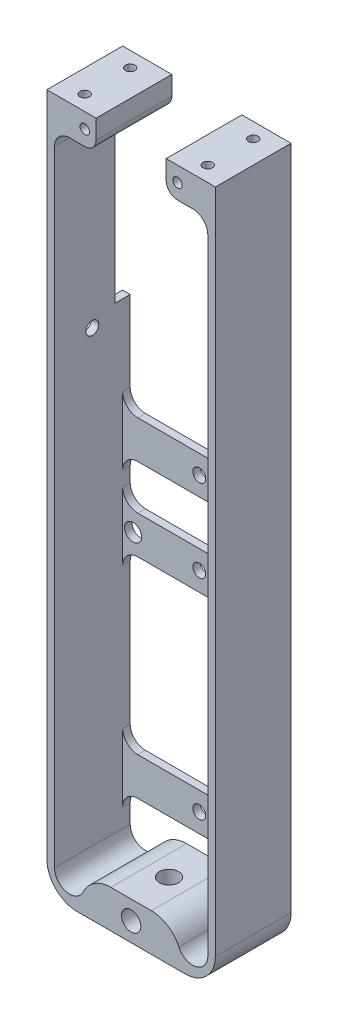
SolidWorks part; units mm, degrees
material "Сплав 2024"
ref_plane "Спереди" through (0, 0, 0) normal (0, 0, 1) x (1, 0, 0)
ref_plane "Сверху" through (0, 0, 0) normal (0, 1, 0) x (1, 0, 0)
ref_plane "Справа" through (0, 0, 0) normal (1, 0, 0) x (0, 0, -1)
sketch "Эскиз1" plane through (0, 0, 0) normal (0, 0, 1) x (1, 0, 0)
  line L0 (-2, -7) -> (42.5, -7)
  line L1 (8, 3) -> (32.5, 3)
  line L2 (0, 0) -> (0, 173)
  line L3 (0, 173) -> (40.5, 173)
  line L4 (40.5, 0) -> (40.5, 173)
  line L5 (42.5, -7) -> (42.5, 175)
  line L6 (-2, 175) -> (42.5, 175)
  line L7 (-2, -7) -> (-2, 175)
  line L8 (8, 0) -> (8, 3)
  line L9 (32.5, 0) -> (32.5, 3)
  arc A0 (0, 0) -> (8, 0) centre (4, 0) ccw
  arc A1 (32.5, 0) -> (40.5, 0) centre (36.5, 0) ccw
  dimension "D6" = 8
  dimension "D7" = 8
  dimension "D1" = 40.5
  dimension "D2" = 170
  dimension "D3" = 10
  dimension "D4" = 2
  dimension "D5" = 2
  dimension "D8" = 2
  dimension "D9" = 7
extrude "Бобышка-Вытянуть1" add sketch "Эскиз1" along normal blind 20
fillet "Скругление1" radius 8 4 edges at (42.5, -7, 10) (-2, -7, 10) (32.5, 3, 10) (8, 3, 10)
sketch "Эскиз2" plane through (0, -7, 0) normal (0, -1, 0) x (1, 0, 0)
  line L0 (20.25, 20) -> (20.25, 0) construction
  line L1 (6, 20) -> (34.5, 20) construction
  line L2 (6, 0) -> (34.5, 0) construction
  line L3 (34.5, 10) -> (6, 10) construction
  line L4 (34.5, 0) -> (34.5, 20) construction
  line L5 (6, 20) -> (6, 0) construction
hole_wizard "Отверстие обработанное метчиком 1/4-201" positions "Эскиз4" profile "Эскиз3" tap size "1/4-20" standard "Ansi Inch"
sketch "Эскиз4" plane through (0, -7, 0) normal (0, -1, 0) x (-1, 0, 0)
  line L0 (-20.25, -20) -> (-20.25, 0) construction
  point P0 (-20.25, -10)
sketch "Эскиз3" plane through (20.25, -7, 10) normal (1, 0, 0) x (0, 0, -1)
  line L0 (0, 0) -> (0, 10)
  line L1 (0, 10) -> (2.5527, 10)
  line L2 (2.5527, 10) -> (2.5527, 0)
  line L5 (2.5527, 0) -> (0, 0)
  line L11 (0, -6.35) -> (0, 107.95) construction
  dimension "Диаметр проходного сверла" = 5.1054
  dimension "Глубина проходного сверла" = 10
cosmetic thread "Отверстие резьбы1" parameters "D2"=6.35
ref_plane "Плоскость1" through (0, 158, 0) normal (0, 1, 0) x (1, 0, 0)
sketch "Эскиз5" plane through (0, 0, 20) normal (0, 0, 1) x (1, 0, 0)
  line L0 (-7.1, 158) -> (-7.1, 132.6982) construction
  line L2 (-7.1, 158) -> (-7.1, 139)
  line L3 (17.5494, 158) -> (-17.5494, 158) construction
  line L4 (0, 173) -> (0, 0) construction
  line L5 (-9.1, 158) -> (-9.1, 139)
  line L6 (-2, 113.3175) -> (-2, 117.4689)
  line L7 (-2, 175) -> (-2, 1) construction
  line L8 (-9.1, 158) -> (-7.1, 158)
  arc A0 (-9.1, 139) -> (-2, 113.3175) centre (40.9, 139) ccw
  arc A1 (-7.1, 139) -> (-2, 117.4689) centre (40.9, 139) ccw
  dimension "D4" = 100
  dimension "D1" = 7.1
  dimension "D2" = 19
  dimension "D3" = 2
extrude "Бобышка-Вытянуть2" add sketch "Эскиз5" against normal up to surface (20 mm away) up to face at (20.25, 55.781, 0)
fillet "Скругление2" radius 100 1 edges at (-2, 113.3175, 10)
sketch "Эскиз6" plane through (0, 0, 20) normal (0, 0, 1) x (1, 0, 0)
  line L2 (0, 173) -> (0, 117.4689)
  line L3 (0, 117.4689) -> (-2, 117.4689)
  line L4 (-2, 170) -> (-2, 117.4689)
  line L5 (42.5, 175) -> (-2, 175)
  line L6 (42.5, 175) -> (42.5, 173)
  line L7 (42.5, 173) -> (0, 173)
  line L8 (-2, 175) -> (-2, 170)
extrude "Вырез-Вытянуть1" cut sketch "Эскиз6" against normal up to next
sketch "Эскиз7" plane through (-9.1, 0, 0) normal (-1, 0, 0) x (0, 0, 1)
  line L0 (10, 158) -> (10, 133.3641) construction
  line L1 (0, 158) -> (20, 158) construction
  circle A0 centre (10, 145.4263) radius 5.25
  dimension "D1" = 10.5
extrude "Вырез-Вытянуть2" cut sketch "Эскиз7" against normal up to next
sketch "Эскиз9" plane through (0, 0, 20) normal (0, 0, 1) x (1, 0, 0)
  line L0 (-6.8233, 133.8533) -> (0, 133.8533)
  line L1 (0, 133.8533) -> (0, 117.4689)
  line L2 (-2, 117.4689) -> (0, 117.4689) construction
  line L3 (-2, 117.4689) -> (0, 117.4689)
  arc A0 (-7.1, 139) -> (-2, 117.4689) centre (40.9, 139) ccw construction
  arc A1 (-6.8233, 133.8533) -> (-2, 117.4689) centre (40.9, 139) ccw
extrude "Бобышка-Вытянуть3" add sketch "Эскиз9" against normal up to surface (20 mm away) up to face at (12.0849, 68.7632, 0)
fillet "Скругление7" radius 4 1 edges at (-6.8233, 133.8533, 10)
sketch "Эскиз10" plane through (0, 0, 20) normal (0, 0, 1) x (1, 0, 0)
  line L0 (17.5494, 158) -> (-17.5494, 158) construction
  line L1 (-9.1, 158) -> (-7.1, 158)
  line L2 (-9.1, 158) -> (-9.1, 172.1367)
  line L3 (-9.1, 172.1367) -> (-7.1, 172.1367)
  line L4 (-7.1, 158) -> (-7.1, 172.1367)
  line L5 (-9.1, 158) -> (-9.1, 139) construction
extrude "Бобышка-Вытянуть4" add sketch "Эскиз10" against normal up to surface (20 mm away) up to face at (11.1424, 73.5841, 0)
sketch "Эскиз11" plane through (-9.1, 0, 0) normal (-1, 0, 0) x (0, 0, 1)
  line L0 (10, 145.4263) -> (10, 162.0459) construction
  circle A0 centre (10, 162.4263) radius 4.1
  dimension "D1" = 8.2
  dimension "D2" = 17
extrude "Вырез-Вытянуть3" cut sketch "Эскиз11" against normal up to next
sketch "Эскиз12" plane through (0, 0, 20) normal (0, 0, 1) x (1, 0, 0)
  line L1 (42.5, 169.6552) -> (-9.1, 169.6552)
  line L2 (42.5, 169.6552) -> (42.5, 175.3281)
  line L3 (42.5, 175.3281) -> (-9.1, 175.3281)
  line L4 (-9.1, 169.6552) -> (-9.1, 175.3281)
extrude "Вырез-Вытянуть4" cut sketch "Эскиз12" against normal up to next
sketch "Эскиз13" plane through (0, 0, 20) normal (0, 0, 1) x (1, 0, 0)
  line L0 (36.5, 175.6552) -> (-3.1, 175.6552)
  line L1 (40.5, 0) -> (40.5, 169.6552) construction
  line L2 (-7.1, 139) -> (-7.1, 169.6552) construction
  line L3 (40.5, 0) -> (40.5, 169.6552) construction
  line L4 (-7.1, 169.6552) -> (-9.1, 169.6552)
  line L5 (42.5, 169.6552) -> (40.5, 169.6552)
  line L6 (-3.1, 173.6552) -> (36.5, 173.6552)
  line L7 (42.5, 1) -> (42.5, 169.6552) construction
  arc A0 (40.5, 169.6552) -> (36.5, 173.6552) centre (36.5, 169.6552) ccw
  arc A1 (-9.1, 169.6552) -> (-3.1, 175.6552) centre (-3.1, 169.6552) cw
  arc A2 (42.5, 169.6552) -> (36.5, 175.6552) centre (36.5, 169.6552) ccw
  arc A4 (-7.1, 169.6552) -> (-3.1, 173.6552) centre (-3.1, 169.6552) cw
  dimension "D1" = 4
  dimension "D2" = 4
extrude "Бобышка-Вытянуть5" add sketch "Эскиз13" against normal up to surface (20 mm away) up to face at (11.1424, 74.3756, 0)
ref_plane "Плоскость2" through (20.25, 0, 0) normal (1, 0, 0) x (0, 0, -1)
ref_plane "Плоскость3" through (0, 0, 10) normal (0, 0, 1) x (1, 0, 0)
sketch "Эскиз14" plane through (0, 0, 20) normal (0, 0, 1) x (1, 0, 0)
  line L1 (-2, 93.3975) -> (-11.1755, 93.3975)
  line L2 (-2, 93.3975) -> (-2, 176.4851)
  line L3 (-2, 176.4851) -> (-11.1755, 176.4851)
  line L4 (-11.1755, 93.3975) -> (-11.1755, 176.4851)
extrude "Вырез-Вытянуть5" cut sketch "Эскиз14" against normal through all
sketch "Эскиз15" plane through (0, 0, 20) normal (0, 0, 1) x (1, 0, 0)
  line L0 (36.5, 175.6552) -> (-2, 175.6552) construction
  line L1 (-2, 173.6552) -> (3, 173.6552)
  line L2 (-2, 173.6552) -> (-2, 168.6552)
  line L3 (-2, 168.6552) -> (3, 168.6552)
  line L4 (3, 173.6552) -> (3, 168.6552)
  dimension "D1" = 7
  dimension "D2" = 5
extrude "Бобышка-Вытянуть6" add sketch "Эскиз15" against normal up to surface (20 mm away) up to face at (19.6984, 71.7247, 0)
fillet "Скругление10" radius 4 1 edges at (3, 173.6552, 10)
sketch "Эскиз17" plane through (0, 0, 20) normal (0, 0, 1) x (1, 0, 0)
  line L0 (0, 133.8533) -> (0, 0) construction
  line L1 (-2, 133.8533) -> (0, 133.8533)
  line L2 (-2, 133.8533) -> (-2, 121.9315)
  line L3 (-2, 121.9315) -> (0, 121.9315)
  line L4 (0, 133.8533) -> (0, 121.9315)
hole_wizard "Отверстие с зазором M31" positions "Эскиз20" profile "Эскиз19" hole size "M3" standard "Ansi Metric"
sketch "Эскиз20" plane through (0, -2.5175, -0.8809) normal (-1, 0, 0) x (0, 0, 1)
  point P0 (10.8809, 121.0204)
sketch "Эскиз19" plane through (0, 118.5029, 10) normal (0, 1, 0) x (0, 0, -1)
  line L0 (0, 0) -> (0, 2)
  line L1 (0, 2) -> (1.7, 2)
  line L2 (1.7, 2) -> (1.7, 0)
  line L5 (1.7, 0) -> (0, 0)
  line L11 (0, -6.35) -> (0, 107.95) construction
  dimension "Диаметр сквозного отверстия" = 3.4
  dimension "Глубина сквозного отверстия" = 2
sketch "Эскиз21" plane through (0, 0, 20) normal (0, 0, 1) x (1, 0, 0)
  line L0 (-2, 168.6552) -> (3, 168.6552) construction
  line L1 (-2, 133.8533) -> (0, 133.8533)
  line L2 (-2, 133.8533) -> (-2, 168.6552)
  line L3 (-2, 168.6552) -> (0, 168.6552)
  line L4 (0, 133.8533) -> (0, 168.6552)
  line L5 (0, 133.8533) -> (-2, 133.8533) construction
extrude "Бобышка-Вытянуть7" add sketch "Эскиз21" against normal up to surface (20 mm away) up to face at (17.4639, 85.659, 0)
sketch "Эскиз23" plane through (0, 0, 20) normal (0, 0, 1) x (1, 0, 0)
  line L0 (42.5, 1) -> (42.5, 169.6552) construction
  line L1 (-2, 175.6552) -> (42.5, 175.6552)
  line L2 (-2, 175.6552) -> (-2, 166.9129)
  line L3 (-2, 166.9129) -> (42.5, 166.9129)
  line L4 (42.5, 175.6552) -> (42.5, 166.9129)
extrude "Вырез-Вытянуть8" cut sketch "Эскиз23" against normal through all
sketch "Эскиз24" plane through (-2, 0, 0) normal (-1, 0, 0) x (0, 0, 1)
  line L0 (10, 118.5029) -> (10, 170.933) construction
sketch "Эскиз30" plane through (0, 0, 20) normal (0, 0, 1) x (1, 0, 0)
  line L1 (40.5, 166.9129) -> (42.5, 166.9129)
  line L2 (40.5, 166.9129) -> (40.5, 177.0029)
  line L3 (40.5, 177.0029) -> (42.5, 177.0029)
  line L4 (42.5, 166.9129) -> (42.5, 177.0029)
  line L5 (0, 166.9129) -> (-2, 166.9129)
  line L6 (0, 166.9129) -> (0, 177.0029)
  line L7 (0, 177.0029) -> (-2, 177.0029)
  line L8 (-2, 166.9129) -> (-2, 177.0029)
  dimension "D1" = 10.09
extrude "Бобышка-Вытянуть9" add sketch "Эскиз30" against normal up to surface (20 mm away) up to face at (20.25, 46.4991, 0)
sketch "Эскиз27" plane through (42.5, 0, 0) normal (1, 0, 0) x (0, 0, -1)
  line L0 (-11.7, 163.0029) -> (-8.3, 163.0029) construction
  line L1 (-11.7, 166.7029) -> (-8.3, 166.7029)
  line L2 (-11.7, 159.3029) -> (-8.3, 159.3029)
  line L3 (-10, 177.0029) -> (-10, 153.6202) construction
  line L5 (0, 177.0029) -> (-20, 177.0029) construction
  arc A0 (-11.7, 166.7029) -> (-11.7, 159.3029) centre (-11.7, 163.0029) ccw
  arc A1 (-8.3, 159.3029) -> (-8.3, 166.7029) centre (-8.3, 163.0029) ccw
  point P2 (-10, 163.0029)
  dimension "D1" = 3.7
  dimension "D2" = 3.4
  dimension "D3" = 14
extrude "Вырез-Вытянуть9" cut sketch "Эскиз27" against normal up to next
ref_plane "Плоскость4" through (0, 0, 4.6) normal (0, 0, 1) x (1, 0, 0)
sketch "Эскиз32" plane through (0, 0, 20) normal (0, 0, 1) x (1, 0, 0)
  line L1 (0, 177.0029) -> (5, 177.0029)
  line L2 (0, 177.0029) -> (0, 174.0029)
  line L3 (0, 174.0029) -> (5, 174.0029)
  line L4 (5, 177.0029) -> (5, 174.0029)
  line L5 (40.5, 177.0029) -> (35.5, 177.0029)
  line L6 (40.5, 177.0029) -> (40.5, 174.0029)
  line L7 (40.5, 174.0029) -> (35.5, 174.0029)
  line L8 (35.5, 177.0029) -> (35.5, 174.0029)
  dimension "D1" = 5
  dimension "D2" = 5
  dimension "D3" = 3
extrude "Бобышка-Вытянуть10" add sketch "Эскиз32" against normal up to surface (20 mm away) up to face at (20.25, 49.382, 0)
fillet "Скругление18" radius 4 2 edges at (40.5, 174.0029, 10) (0, 174.0029, 10)
sketch "Эскиз33" plane through (0, 0, 0) normal (0, 0, -1) x (-1, 0, 0)
  line L0 (0, 170.0029) -> (0, 0) construction
  line L2 (0, 8.9054) -> (-40.5, 8.9054)
  line L3 (0, 8.9054) -> (0, 18.9054)
  line L4 (0, 18.9054) -> (-40.5, 18.9054)
  line L5 (-40.5, 8.9054) -> (-40.5, 18.9054)
  line L6 (0, 8.9054) -> (-40.5, 18.9054) construction
  line L7 (0, 18.9054) -> (-40.5, 8.9054) construction
  line L8 (-40.5, 0) -> (-40.5, 170.0029) construction
  line L10 (0, 85.9613) -> (-40.5, 85.9613)
  line L11 (0, 85.9613) -> (0, 95.9613)
  line L12 (0, 95.9613) -> (-40.5, 95.9613)
  line L13 (-40.5, 85.9613) -> (-40.5, 95.9613)
  line L14 (0, 85.9613) -> (-40.5, 95.9613) construction
  line L15 (0, 95.9613) -> (-40.5, 85.9613) construction
  line L16 (-40.5, 64.1504) -> (0, 64.1504)
  line L17 (-40.5, 64.1504) -> (-40.5, 74.1504)
  line L18 (-40.5, 74.1504) -> (0, 74.1504)
  line L19 (0, 64.1504) -> (0, 74.1504)
  line L20 (0, 74.1504) -> (-40.5, 64.1504) construction
  point P0 (-20.25, 90.9613)
  point P2 (-20.25, 13.9054)
  point P5 (-20.25, 69.1504)
  point P8 (-20.25, 90.9613)
  point P10 (-20.25, 146.2063)
  point P12 (-20.25, 13.9054)
  point P26 (-20.25, 69.1504)
  dimension "D1" = 10
  dimension "D2" = 10
  dimension "D3" = 10
extrude "Бобышка-Вытянуть11" add sketch "Эскиз33" against normal blind 2
fillet "Скругление19" radius 4 12 edges at (0, 8.9054, 1) (40.5, 8.9054, 1) (0, 18.9054, 1) (40.5, 18.9054, 1) (40.5, 95.9613, 1) (40.5, 85.9613, 1) (0, 85.9613, 1) (0, 95.9613, 1) (40.5, 74.1504, 1) (40.5, 64.1504, 1) (0, 64.1504, 1) (0, 74.1504, 1)
hole_wizard "Отверстие с зазором M33" positions "Эскиз35" profile "Эскиз34" hole size "M3" standard "Ansi Metric"
sketch "Эскиз35" plane through (0, 0, 0) normal (0, 0, -1) x (-1, 0, 0)
  line L0 (0, 74.1504) -> (-40.5, 64.1504) construction
  point P14 (-20.25, 13.9054)
  point P17 (-20.25, 69.1504)
  point P21 (-20.25, 90.9613)
sketch "Эскиз34" plane through (20.25, 13.9054, 0) normal (1, 0, 0) x (0, 1, 0)
  line L0 (0, 0) -> (0, 3.0215)
  line L1 (0, 3.0215) -> (1.7, 2)
  line L2 (1.7, 2) -> (1.7, 0)
  line L5 (1.7, 0) -> (0, 0)
  line L10 (0, 3.0215) -> (-1.7, 2) construction
  line L11 (0, -6.35) -> (0, 107.95) construction
  dimension "Диаметр отверстия" = 3.4
  dimension "Глубина отверстия" = 2
  dimension "Угол заточки сверла" = 118
sketch "Эскиз36" plane through (0, 0, 20) normal (0, 0, 1) x (1, 0, 0)
  line L0 (42.5, 1) -> (42.5, 177.0029) construction
  line L1 (42.5, 158.0029) -> (0, 158.0029)
  line L2 (42.5, 158.0029) -> (42.5, 177.0029)
  line L3 (42.5, 177.0029) -> (0, 177.0029)
  line L4 (0, 158.0029) -> (0, 177.0029)
  line L5 (0, 170.0029) -> (0, 0) construction
  line L6 (42.5, 177.0029) -> (35.5, 177.0029) construction
  dimension "D1" = 19
extrude "Вырез-Вытянуть11" cut sketch "Эскиз36" against normal up to surface (20 mm away) up to face at (18.55, 13.9054, 0)
sketch "Эскиз37" plane through (0, 0, 20) normal (0, 0, 1) x (1, 0, 0)
  line L0 (0, 177.0029) -> (-2, 177.0029) construction
  line L1 (42.5, 158.0029) -> (40.5, 158.0029)
  line L2 (0, 169.0029) -> (0, 177.0029)
  line L3 (40.5, 147.897) -> (0, 147.897) construction
  line L4 (29.5, 177.0029) -> (42.5, 177.0029)
  line L5 (42.5, 177.0029) -> (42.5, 158.0029)
  line L6 (40.5, 0) -> (40.5, 158.0029) construction
  line L7 (0, 177.0029) -> (0, 0) construction
  line L8 (20.25, 147.897) -> (20.25, 154.9149) construction
  line L9 (29.5, 169.0029) -> (40.5, 169.0029)
  line L10 (40.5, 169.0029) -> (40.5, 158.0029)
  line L11 (0, 177.0029) -> (11, 177.0029)
  line L12 (11, 169.0029) -> (0, 169.0029)
  line L13 (29.5, 169.0029) -> (29.5, 177.0029)
  line L14 (11, 177.0029) -> (11, 169.0029)
  dimension "D1" = 8
  dimension "D2" = 13
extrude "Бобышка-Вытянуть12" add sketch "Эскиз37" against normal up to surface (20 mm away) up to face at (20.25, 87.0739, 0)
fillet "Скругление21" radius 4 2 edges at (40.5, 169.0029, 10) (0, 169.0029, 10)
fillet "Скругление22" radius 3 2 edges at (11, 169.0029, 10) (29.5, 169.0029, 10)
sketch "Эскиз41" plane through (0, 0, 20) normal (0, 0, 1) x (1, 0, 0)
  line L0 (20.25, -7) -> (20.25, 1.5339) construction
  line L1 (6, -7) -> (34.5, -7) construction
  point P4 (20.25, -2)
  dimension "D1" = 5
hole_wizard "Отверстие обработанное метчиком 1/4-202" positions "Эскиз43" profile "Эскиз42" tap size "1/4-20" standard "Ansi Inch"
sketch "Эскиз43" plane through (0, 0, 20) normal (0, 0, 1) x (1, 0, 0)
  point P0 (20.25, -2)
sketch "Эскиз42" plane through (20.25, -2, 20) normal (1, 0, 0) x (0, -1, 0)
  line L0 (0, 0) -> (0, 7.5338)
  line L1 (0, 7.5338) -> (2.5527, 6)
  line L2 (2.5527, 6) -> (2.5527, 0)
  line L5 (2.5527, 0) -> (0, 0)
  line L10 (0, 7.5338) -> (-2.5527, 6) construction
  line L11 (0, -6.35) -> (0, 107.95) construction
  dimension "Диаметр сверла" = 5.1054
  dimension "Глубина сверла" = 6
  dimension "Угол заточки сверла" = 118
cosmetic thread "Отверстие резьбы2" parameters "D1"=6, "D2"=6.35
sketch "Эскиз44" plane through (-2, 0, 0) normal (-1, 0, 0) x (0, 0, 1)
  line L0 (10, 177.0029) -> (10, 164.3494) construction
  line L1 (0, 177.0029) -> (20, 177.0029) construction
  point P4 (10, 172.0029)
  dimension "D1" = 5
sketch "Эскиз48" plane through (0, 0, 20) normal (0, 0, 1) x (1, 0, 0)
  line L0 (42.5, 173.0029) -> (-2, 173.0029) construction
  line L1 (42.5, 1) -> (42.5, 177.0029) construction
  line L2 (-2, 177.0029) -> (-2, 1) construction
  line L3 (11, 177.0029) -> (-2, 177.0029) construction
  point P8 (8, 173.0029)
  point P9 (32.5, 173.0029)
  dimension "D1" = 4
  dimension "D2" = 10
  dimension "D3" = 10
hole_wizard "Отверстие обработанное метчиком M3x0.52" positions "Эскиз50" profile "Эскиз49" tap size "M3x0.5" standard "Ansi Metric" end condition through all
sketch "Эскиз50" plane through (0, 0, 20) normal (0, 0, 1) x (1, 0, 0)
  point P0 (8, 173.0029)
  point P3 (32.5, 173.0029)
sketch "Эскиз49" plane through (8, 173.0029, 20) normal (1, 0, 0) x (0, -1, 0)
  line L0 (0, 0) -> (0, 20)
  line L1 (0, 20) -> (1.25, 20)
  line L2 (1.25, 20) -> (1.25, 0)
  line L5 (1.25, 0) -> (0, 0)
  line L11 (0, -6.35) -> (0, 107.95) construction
  dimension "Диаметр резьбы" = 2.5
  dimension "Глубина проходного сверла" = 20
sketch "Эскиз51" plane through (0, 0, 0) normal (0, 0, -1) x (-1, 0, 0)
  line L0 (2, 177.0029) -> (2, 1) construction
  line L1 (2, 121.1707) -> (-2.0724, 121.1707)
  line L2 (2, 121.1707) -> (2, 167.5284)
  line L3 (2, 167.5284) -> (-2.0724, 167.5284)
  line L4 (-2.0724, 121.1707) -> (-2.0724, 167.5284)
extrude "Вырез-Вытянуть13" cut sketch "Эскиз51" against normal blind 4
hole_wizard "Отверстие обработанное метчиком M3x0.53" positions "Эскиз53" profile "Эскиз52" tap size "M3x0.5" standard "Ansi Metric"
sketch "Эскиз53" plane through (-2, 0, 0) normal (-1, 0, 0) x (0, 0, 1)
  point P0 (10, 169.5029)
sketch "Эскиз52" plane through (-2, 169.5029, 10) normal (0, 1, 0) x (0, 0, 1)
  line L0 (0, 0) -> (0, 9.2511)
  line L1 (0, 9.2511) -> (1.25, 8.5)
  line L2 (1.25, 8.5) -> (1.25, 0)
  line L5 (1.25, 0) -> (0, 0)
  line L10 (0, 9.2511) -> (-1.25, 8.5) construction
  line L11 (0, -6.35) -> (0, 107.95) construction
  dimension "Диаметр сверла" = 2.5
  dimension "Глубина сверла" = 8.5
  dimension "Угол заточки сверла" = 118
sketch "Эскиз54" plane through (0, 0, 0) normal (0, 0, -1) x (-1, 0, 0)
  circle A0 centre (-37.7506, 13.9054) radius 2.25
  circle A1 centre (-2.7494, 69.1504) radius 2.25
  circle A2 centre (-37.7506, 90.9613) radius 2.25
  dimension "D1" = 4.5
  dimension "D2" = 4.5
  dimension "D3" = 4.5
extrude "Вырез-Вытянуть14" cut sketch "Эскиз54" against normal up to next
hole_wizard "Отверстие обработанное метчиком M3x0.54" positions "Эскиз57" profile "Эскиз56" tap size "M3x0.5" standard "Ansi Metric"
sketch "Эскиз57" plane through (0, 177.0029, 0) normal (0, 1, 0) x (1, 0, 0)
  point P0 (4, -4)
  point P3 (4, -16)
  point P6 (36.5, -4)
  point P9 (36.5, -16)
sketch "Эскиз56" plane through (4, 177.0029, 4) normal (1, 0, 0) x (0, 0, 1)
  line L0 (0, 0) -> (0, 9.2511)
  line L1 (0, 9.2511) -> (1.25, 8.5)
  line L2 (1.25, 8.5) -> (1.25, 0)
  line L5 (1.25, 0) -> (0, 0)
  line L10 (0, 9.2511) -> (-1.25, 8.5) construction
  line L11 (0, -6.35) -> (0, 107.95) construction
  dimension "Диаметр сверла" = 2.5
  dimension "Глубина сверла" = 8.5
  dimension "Угол заточки сверла" = 118
sketch "Эскиз29" plane through (42.5, 0, 0) normal (1, 0, 0) x (0, 0, -1)
  line B0 (-6.5886, 80.4254) -> (-6.3563, 80.4254)
  line B1 (-6.3563, 79.3221) -> (-6.5886, 79.3221)
  line B2 (-13.9862, 82.8197) -> (-13.9862, 85.4096)
  line B3 (-11.4081, 88.4523) -> (-11.3847, 88.4523)
  line B4 (-8.7255, 85.2586) -> (-8.7255, 83.2844)
  line B5 (-8.7255, 83.2844) -> (-6.2634, 83.2844)
  line B6 (-6.2634, 82.3669) -> (-13.5217, 82.3669)
  line B7 (-11.35, 87.5231) -> (-11.3732, 87.5231)
  line B8 (-13.1385, 85.3399) -> (-13.1385, 83.2844)
  line B9 (-13.1385, 83.2844) -> (-9.5615, 83.2844)
  line B10 (-9.5615, 83.2844) -> (-9.5615, 85.2934)
  line B11 (-13.9862, 90.2857) -> (-13.9862, 93.3285)
  line B12 (-11.5706, 96.2666) -> (-11.5474, 96.2666)
  line B13 (-9.1899, 94.0948) -> (-6.5886, 96.1156)
  line B14 (-6.0428, 95.3724) -> (-9.0157, 93.0846)
  line B15 (-9.0157, 93.0846) -> (-9.0157, 90.7503)
  line B16 (-9.0157, 90.7503) -> (-6.2634, 90.7503)
  line B17 (-6.2634, 89.8328) -> (-13.5217, 89.8328)
  line B18 (-11.5126, 95.3374) -> (-11.5357, 95.3374)
  line B19 (-13.1385, 93.2587) -> (-13.1385, 90.7503)
  line B20 (-13.1385, 90.7503) -> (-9.8402, 90.7503)
  line B21 (-9.8402, 90.7503) -> (-9.8402, 93.2471)
  line B22 (-9.8983, 97.0327) -> (-9.9216, 97.0327)
  line B23 (-9.9447, 105.3245) -> (-9.9216, 105.3245)
  line B24 (-9.8983, 104.3723) -> (-9.9216, 104.3723)
  line B25 (-9.9447, 97.985) -> (-9.9216, 97.985)
  line B26 (-15.2212, 75.6776) -> (-15.2445, 75.6776)
  line B27 (-15.2445, 79.6028) -> (-15.2212, 79.6028)
  line B28 (-13.9861, 7.7564) -> (-13.9861, 10.0094)
  line B29 (-13.9861, 10.0094) -> (-10.688, 10.0094)
  line B30 (-10.688, 10.0094) -> (-13.9861, 12.8082)
  line B31 (-13.9861, 12.8082) -> (-13.9861, 15.4793)
  line B32 (-13.9861, 15.4793) -> (-10.4905, 12.4018)
  line B33 (-10.4905, 12.4018) -> (-5.8568, 15.5837)
  line B34 (-5.8568, 15.5837) -> (-5.8568, 12.8779)
  line B35 (-5.8568, 12.8779) -> (-8.8763, 10.8339)
  line B36 (-8.8763, 10.8339) -> (-7.9589, 10.0094)
  line B37 (-7.9589, 10.0094) -> (-5.8568, 10.0094)
  line B38 (-5.8568, 10.0094) -> (-5.8568, 7.7564)
  line B39 (-5.8568, 7.7564) -> (-13.9861, 7.7564)
  line B40 (-13.9861, 16.2802) -> (-13.9861, 18.5448)
  line B41 (-13.9861, 18.5448) -> (-5.8568, 18.5448)
  line B42 (-5.8568, 18.5448) -> (-5.8568, 16.2802)
  line B43 (-5.8568, 16.2802) -> (-13.9861, 16.2802)
  line B44 (-13.9861, 20.031) -> (-13.9861, 22.1332)
  line B45 (-13.9861, 22.1332) -> (-9.6892, 25.4777)
  line B46 (-9.6892, 25.4777) -> (-13.9861, 25.4777)
  line B47 (-13.9861, 25.4777) -> (-13.9861, 27.7074)
  line B48 (-13.9861, 27.7074) -> (-5.8568, 27.7074)
  line B49 (-5.8568, 27.7074) -> (-5.8568, 25.7331)
  line B50 (-5.8568, 25.7331) -> (-10.3163, 22.2608)
  line B51 (-10.3163, 22.2608) -> (-5.8568, 22.2608)
  line B52 (-5.8568, 22.2608) -> (-5.8568, 20.031)
  line B53 (-5.8568, 20.031) -> (-13.9861, 20.031)
  line B54 (-13.9861, 29.147) -> (-13.9861, 35.6853)
  line B55 (-13.9861, 35.6853) -> (-12.07, 35.6853)
  line B56 (-12.07, 35.6853) -> (-12.07, 31.3768)
  line B57 (-12.07, 31.3768) -> (-10.8389, 31.3768)
  line B58 (-10.8389, 31.3768) -> (-10.8389, 35.2789)
  line B59 (-10.8389, 35.2789) -> (-9.0622, 35.2789)
  line B60 (-9.0622, 35.2789) -> (-9.0622, 31.3768)
  line B61 (-9.0622, 31.3768) -> (-7.773, 31.3768)
  line B62 (-7.773, 31.3768) -> (-7.773, 35.7433)
  line B63 (-7.773, 35.7433) -> (-5.8568, 35.7433)
  line B64 (-5.8568, 35.7433) -> (-5.8568, 29.147)
  line B65 (-5.8568, 29.147) -> (-13.9861, 29.147)
  line B66 (-13.9861, 36.8928) -> (-13.9861, 39.2735)
  line B67 (-13.9861, 39.2735) -> (-10.8389, 41.2129)
  line B68 (-10.8389, 41.2129) -> (-13.9861, 43.1523)
  line B69 (-13.9861, 43.1523) -> (-13.9861, 45.533)
  line B70 (-13.9861, 45.533) -> (-5.8568, 45.533)
  line B71 (-5.8568, 45.533) -> (-5.8568, 43.2917)
  line B72 (-5.8568, 43.2917) -> (-10.5253, 43.2917)
  line B73 (-10.5253, 43.2917) -> (-7.3433, 41.2129)
  line B74 (-7.3433, 41.2129) -> (-7.3433, 41.1664)
  line B75 (-7.3433, 41.1664) -> (-10.5022, 39.0992)
  line B76 (-10.5022, 39.0992) -> (-5.8568, 39.0992)
  line B77 (-5.8568, 39.0992) -> (-5.8568, 36.8928)
  line B78 (-5.8568, 36.8928) -> (-13.9861, 36.8928)
  line B79 (-14.0442, 49.7831) -> (-14.0442, 51.9548)
  line B80 (-14.0442, 51.9548) -> (-5.8568, 55.4156)
  line B81 (-5.8568, 55.4156) -> (-5.8568, 53)
  line B82 (-5.8568, 53) -> (-7.3086, 52.4077)
  line B83 (-7.3086, 52.4077) -> (-7.3086, 49.2722)
  line B84 (-7.3086, 49.2722) -> (-5.8568, 48.6914)
  line B85 (-5.8568, 48.6914) -> (-5.8568, 46.3223)
  line B86 (-5.8568, 46.3223) -> (-14.0442, 49.7831)
  line B87 (-9.0622, 51.7574) -> (-11.3731, 50.8516)
  line B88 (-11.3731, 50.8516) -> (-9.0622, 49.934)
  line B89 (-9.0622, 49.934) -> (-9.0622, 51.7574)
  line B90 (-12.0118, 57.1456) -> (-12.0118, 54.7068)
  line B91 (-12.0118, 54.7068) -> (-13.9861, 54.7068)
  line B92 (-13.9861, 54.7068) -> (-13.9861, 61.8374)
  line B93 (-13.9861, 61.8374) -> (-12.0118, 61.8374)
  line B94 (-12.0118, 61.8374) -> (-12.0118, 59.3986)
  line B95 (-12.0118, 59.3986) -> (-5.8568, 59.3986)
  line B96 (-5.8568, 59.3986) -> (-5.8568, 57.1456)
  line B97 (-5.8568, 57.1456) -> (-12.0118, 57.1456)
  line B98 (-13.9861, 62.8706) -> (-13.9861, 65.1352)
  line B99 (-13.9861, 65.1352) -> (-5.8568, 65.1352)
  line B100 (-5.8568, 65.1352) -> (-5.8568, 62.8706)
  line B101 (-5.8568, 62.8706) -> (-13.9861, 62.8706)
  line B102 (-13.9861, 66.6215) -> (-13.9861, 68.8744)
  line B103 (-13.9861, 68.8744) -> (-10.688, 68.8744)
  line B104 (-10.688, 68.8744) -> (-13.9861, 71.6733)
  line B105 (-13.9861, 71.6733) -> (-13.9861, 74.3444)
  line B106 (-13.9861, 74.3444) -> (-10.4905, 71.2669)
  line B107 (-10.4905, 71.2669) -> (-5.8568, 74.4489)
  line B108 (-5.8568, 74.4489) -> (-5.8568, 71.7429)
  line B109 (-5.8568, 71.7429) -> (-8.8763, 69.699)
  line B110 (-8.8763, 69.699) -> (-7.9589, 68.8744)
  line B111 (-7.9589, 68.8744) -> (-5.8568, 68.8744)
  line B112 (-5.8568, 68.8744) -> (-5.8568, 66.6215)
  line B113 (-5.8568, 66.6215) -> (-13.9861, 66.6215)
  spline B114 degree 3 poles (-7.1345, 79.8795) (-7.1345, 80.193) (-6.9021, 80.4254) (-6.5886, 80.4254) knots 0 0 0 0 1 1 1 1
  spline B115 degree 3 poles (-6.3563, 80.4254) (-6.0428, 80.4254) (-5.7989, 80.193) (-5.7989, 79.8795) knots 2 2 2 2 3 3 3 3
  spline B116 degree 3 poles (-5.7989, 79.8795) (-5.7989, 79.5543) (-6.0428, 79.3221) (-6.3563, 79.3221) knots 3 3 3 3 4 4 4 4
  spline B117 degree 3 poles (-6.5886, 79.3221) (-6.9021, 79.3221) (-7.1345, 79.5543) (-7.1345, 79.8795) knots 5 5 5 5 6 6 6 6
  spline B118 degree 3 poles (-13.5217, 82.3669) (-13.7771, 82.3669) (-13.9862, 82.576) (-13.9862, 82.8197) knots 0 0 0 0 1 1 1 1
  spline B119 degree 3 poles (-13.9862, 85.4096) (-13.9862, 87.2445) (-13.0106, 88.4523) (-11.4081, 88.4523) knots 2 2 2 2 3 3 3 3
  spline B120 degree 3 poles (-11.3847, 88.4523) (-9.6312, 88.4523) (-8.7255, 86.989) (-8.7255, 85.2586) knots 4 4 4 4 5 5 5 5
  spline B121 degree 3 poles (-6.2634, 83.2844) (-6.0079, 83.2844) (-5.7989, 83.0753) (-5.7989, 82.8197) knots 7 7 7 7 8 8 8 8
  spline B122 degree 3 poles (-5.7989, 82.8197) (-5.7989, 82.576) (-6.0079, 82.3669) (-6.2634, 82.3669) knots 8 8 8 8 9 9 9 9
  spline B123 degree 3 poles (-9.5615, 85.2934) (-9.5615, 86.6406) (-10.2815, 87.5231) (-11.35, 87.5231) knots 0 0 0 0 1 1 1 1
  spline B124 degree 3 poles (-11.3732, 87.5231) (-12.5345, 87.5231) (-13.1385, 86.6523) (-13.1385, 85.3399) knots 2 2 2 2 3 3 3 3
  spline B125 degree 3 poles (-13.5217, 89.8328) (-13.7771, 89.8328) (-13.9862, 90.0419) (-13.9862, 90.2857) knots 0 0 0 0 1 1 1 1
  spline B126 degree 3 poles (-13.9862, 93.3285) (-13.9862, 94.3272) (-13.6843, 95.1285) (-13.1733, 95.6395) knots 2 2 2 2 3 3 3 3
  spline B127 degree 3 poles (-13.1733, 95.6395) (-12.7784, 96.0342) (-12.2094, 96.2666) (-11.5706, 96.2666) knots 3 3 3 3 4 4 4 4
  spline B128 degree 3 poles (-11.5474, 96.2666) (-10.212, 96.2666) (-9.4338, 95.3608) (-9.1899, 94.0948) knots 5 5 5 5 6 6 6 6
  spline B129 degree 3 poles (-6.5886, 96.1156) (-6.4839, 96.2085) (-6.3794, 96.2666) (-6.2518, 96.2666) knots 7 7 7 7 8 8 8 8
  spline B130 degree 3 poles (-6.2518, 96.2666) (-6.0079, 96.2666) (-5.7989, 96.0342) (-5.7989, 95.8021) knots 8 8 8 8 9 9 9 9
  spline B131 degree 3 poles (-5.7989, 95.8021) (-5.7989, 95.6162) (-5.9034, 95.4768) (-6.0428, 95.3724) knots 9 9 9 9 10 10 10 10
  spline B132 degree 3 poles (-6.2634, 90.7503) (-6.0079, 90.7503) (-5.7989, 90.5412) (-5.7989, 90.2857) knots 13 13 13 13 14 14 14 14
  spline B133 degree 3 poles (-5.7989, 90.2857) (-5.7989, 90.0419) (-6.0079, 89.8328) (-6.2634, 89.8328) knots 14 14 14 14 15 15 15 15
  spline B134 degree 3 poles (-9.8402, 93.2471) (-9.8402, 94.4666) (-10.4674, 95.3374) (-11.5126, 95.3374) knots 0 0 0 0 1 1 1 1
  spline B135 degree 3 poles (-11.5357, 95.3374) (-12.5345, 95.3374) (-13.1385, 94.5711) (-13.1385, 93.2587) knots 2 2 2 2 3 3 3 3
  spline B136 degree 3 poles (-9.9216, 97.0327) (-12.1629, 97.0327) (-14.1256, 98.7167) (-14.1256, 101.1903) knots 1 1 1 1 2 2 2 2
  spline B137 degree 3 poles (-14.1256, 101.1903) (-14.1256, 103.6639) (-12.1861, 105.3245) (-9.9447, 105.3245) knots 2 2 2 2 3 3 3 3
  spline B138 degree 3 poles (-9.9216, 105.3245) (-7.6803, 105.3245) (-5.7176, 103.6406) (-5.7176, 101.167) knots 4 4 4 4 5 5 5 5
  spline B139 degree 3 poles (-5.7176, 101.167) (-5.7176, 98.6934) (-7.6569, 97.0327) (-9.8983, 97.0327) knots 5 5 5 5 6 6 6 6
  spline B140 degree 3 poles (-9.9216, 104.3723) (-11.768, 104.3723) (-13.2778, 103.0252) (-13.2778, 101.167) knots 1 1 1 1 2 2 2 2
  spline B141 degree 3 poles (-13.2778, 101.167) (-13.2778, 99.3089) (-11.7913, 97.985) (-9.9447, 97.985) knots 2 2 2 2 3 3 3 3
  spline B142 degree 3 poles (-9.9216, 97.985) (-8.075, 97.985) (-6.5653, 99.3321) (-6.5653, 101.1903) knots 4 4 4 4 5 5 5 5
  spline B143 degree 3 poles (-6.5653, 101.1903) (-6.5653, 103.0483) (-8.0518, 104.3723) (-9.8983, 104.3723) knots 5 5 5 5 6 6 6 6
  spline B144 degree 3 poles (-15.2445, 75.6776) (-16.3245, 75.6776) (-17.1954, 76.5601) (-17.1954, 77.6401) knots 1 1 1 1 2 2 2 2
  spline B145 degree 3 poles (-17.1954, 77.6401) (-17.1954, 78.7202) (-16.3245, 79.6028) (-15.2445, 79.6028) knots 2 2 2 2 3 3 3 3
  spline B146 degree 3 poles (-15.2212, 79.6028) (-14.1412, 79.6028) (-13.2702, 78.7202) (-13.2702, 77.6401) knots 4 4 4 4 5 5 5 5
  spline B147 degree 3 poles (-13.2702, 77.6401) (-13.2702, 76.5601) (-14.1412, 75.6776) (-15.2212, 75.6776) knots 5 5 5 5 6 6 6 6
sketch_block_instance "Блок3-1"
sketch_block "Блок3"
equation "\"D1@Эскиз5\"=5.5+1.6"
